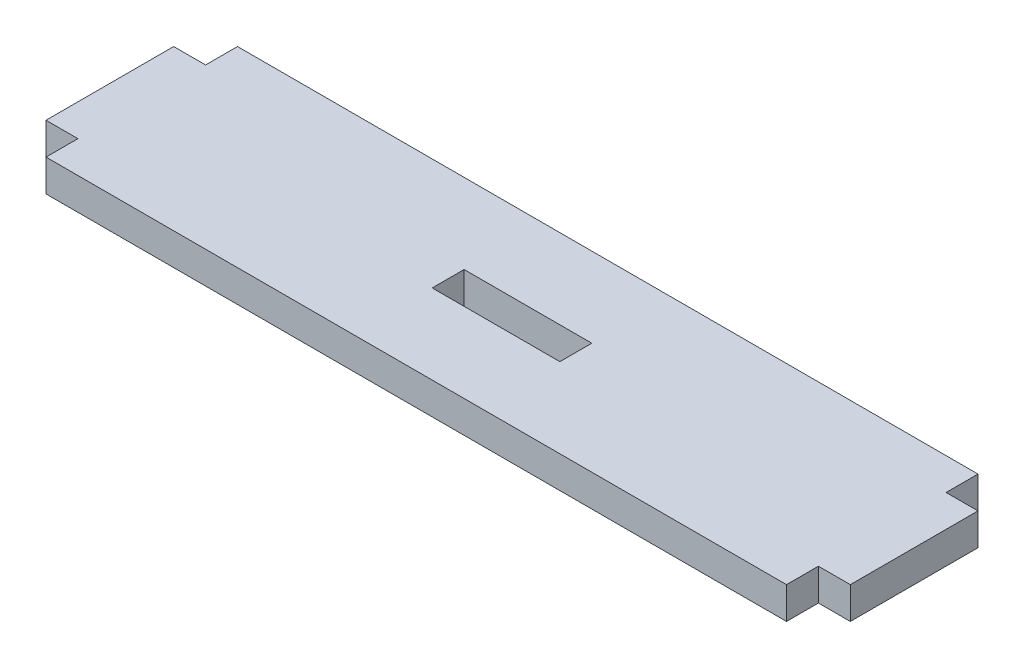
SolidWorks part; units mm, degrees
ref_plane "Front Plane" through (0, 0, 0) normal (0, 0, 1) x (1, 0, 0)
ref_plane "Top Plane" through (0, 0, 0) normal (0, 1, 0) x (1, 0, 0)
ref_plane "Right Plane" through (0, 0, 0) normal (1, 0, 0) x (0, 0, -1)
sketch "Sketch2" plane through (0, 0, 0) normal (0, 1, 0) x (1, 0, 0)
  line L0 (46.5893, 13.309) -> (51.5893, 13.309)
  line L1 (27.5893, 13.309) -> (46.5893, 13.309)
  line L3 (-20.9107, -16.691) -> (95.0893, -16.691)
  line L4 (95.0893, 13.309) -> (95.0893, 8.309)
  line L5 (95.0893, 8.309) -> (100.0893, 8.309)
  line L7 (95.0893, -11.691) -> (100.0893, -11.691)
  line L8 (100.0893, 8.309) -> (100.0893, -11.691)
  line L13 (95.0893, -11.691) -> (95.0893, -16.691)
  line L18 (51.5893, 13.309) -> (95.0893, 13.309)
  line L19 (37.0893, -16.691) -> (37.0893, 34.6569) construction
  line L28 (100.0893, -1.691) -> (-25.9107, -1.691) construction
  line L35 (22.5893, 13.309) -> (-20.9107, 13.309)
  line L36 (-20.9107, -11.691) -> (-20.9107, -16.691)
  line L37 (-25.9107, 8.309) -> (-25.9107, -11.691)
  line L38 (-20.9107, -11.691) -> (-25.9107, -11.691)
  line L39 (-20.9107, 8.309) -> (-25.9107, 8.309)
  line L40 (-20.9107, 13.309) -> (-20.9107, 8.309)
  line L41 (27.5893, 13.309) -> (22.5893, 13.309)
  line L49 (27.0893, -4.191) -> (47.0893, -4.191)
  line L50 (27.0893, -4.191) -> (27.0893, 0.809)
  line L51 (27.0893, 0.809) -> (47.0893, 0.809)
  line L52 (47.0893, -4.191) -> (47.0893, 0.809)
  line L53 (27.0893, -4.191) -> (47.0893, 0.809) construction
  line L54 (27.0893, 0.809) -> (47.0893, -4.191) construction
  point P2 (37.0893, -1.691)
  point P46 (37.0893, 13.309)
  dimension "D1" = 5
  dimension "D2" = 30
  dimension "D3" = 5
  dimension "D4" = 20
  dimension "D5" = 5
  dimension "D6" = 116
  dimension "D7" = 20
extrude "Boss-Extrude1" add sketch "Sketch2" along normal blind 5
